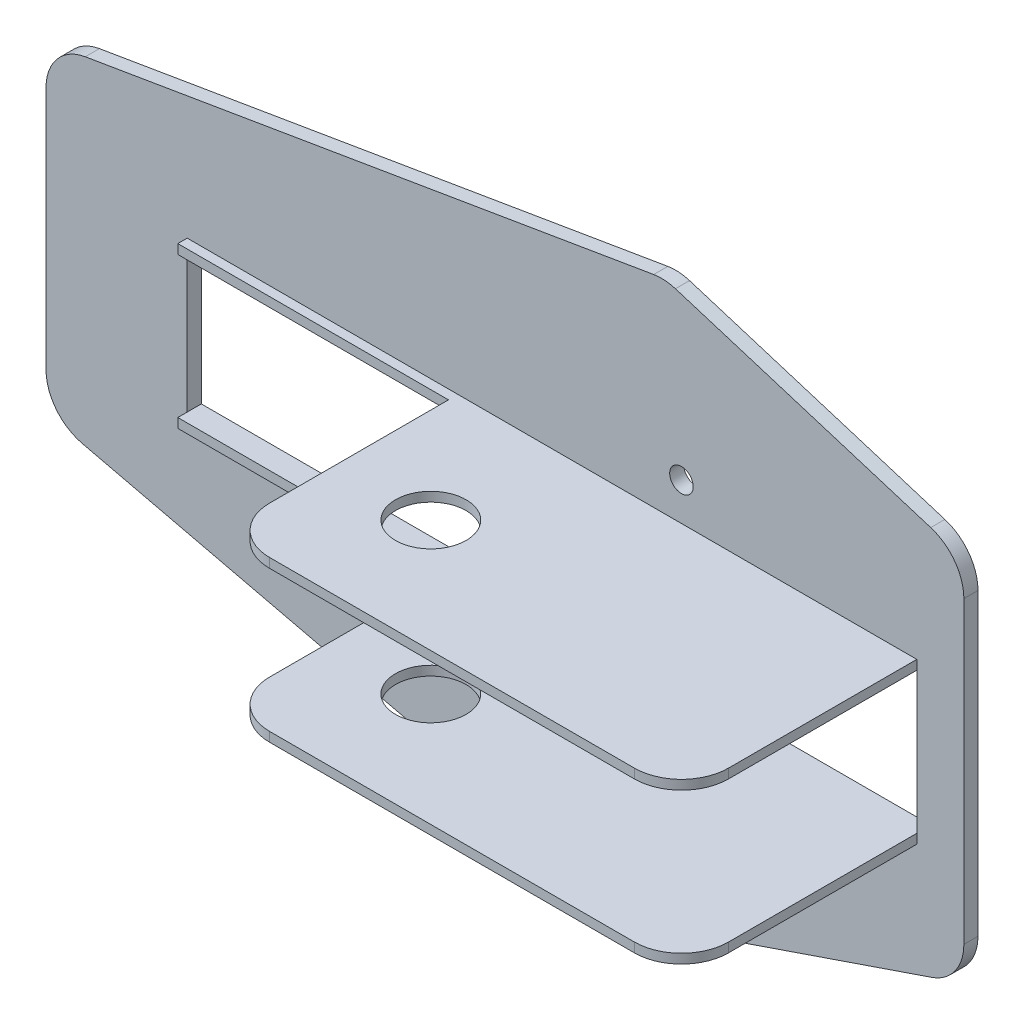
SolidWorks part; units mm, degrees
ref_plane "Płaszczyzna przednia" through (0, 0, 0) normal (0, 0, 1) x (1, 0, 0)
ref_plane "Płaszczyzna górna" through (0, 0, 0) normal (0, 1, 0) x (1, 0, 0)
ref_plane "Płaszczyzna prawa" through (0, 0, 0) normal (1, 0, 0) x (0, 0, -1)
sketch "Szkic1" plane through (0, 0, 0) normal (0, 0, 1) x (1, 0, 0)
  line L1 (-130, -75) -> (130, -75)
  line L2 (-130, -75) -> (-130, 75)
  line L3 (-130, 75) -> (130, 75)
  line L4 (130, -75) -> (130, 75)
  line L5 (-130, -75) -> (130, 75) construction
  line L6 (-130, 75) -> (130, -75) construction
  point P0 (0, 0)
  dimension "D1" = 150
  dimension "D2" = 260
extrude "Dodanie-wyciągnięcie1" add sketch "Szkic1" along normal blind 3
sketch "Szkic2" plane through (0, 0, 3) normal (0, 0, 1) x (1, 0, 0)
  line L0 (130, -75) -> (130, 75) construction
  line L2 (-35, -15) -> (120, -15)
  line L3 (-35, -15) -> (-35, 15)
  line L4 (-35, 15) -> (120, 15)
  line L5 (120, -15) -> (120, 15)
  line L6 (-35, -15) -> (120, 15) construction
  line L7 (-35, 15) -> (120, -15) construction
  circle A0 centre (70, 25) radius 2.5
  circle A1 centre (70, -25) radius 2.5
  point P7 (42.5, 0)
  dimension "D1" = 5
  dimension "D2" = 5
  dimension "D3" = 25
  dimension "D4" = 25
  dimension "D5" = 60
  dimension "D6" = 60
  dimension "D7" = 155
  dimension "D8" = 30
  dimension "D9" = 165
  dimension "D10" = 15
extrude "Wytnij-wyciągnięcie1" cut sketch "Szkic2" against normal blind 3
ref_plane "Płaszczyzna1" through (130, 75, 3) normal (0, 1, 0) x (1, 0, 0)
sketch "Szkic4" plane through (0, 0, 0) normal (0, 0, -1) x (-1, 0, 0)
  line L0 (-130, -30.4364) -> (-130, 33.1787)
  line L1 (-130, -75) -> (-130, 75) construction
  line L2 (-122.9621, 42.73) -> (-68.7231, 59.5512)
  line L3 (-64.1018, 59.8614) -> (56.6591, 39.5438)
  line L4 (65, 29.6824) -> (65, -22.1974)
  line L5 (57.2986, -31.9296) -> (-60.4177, -59.7322)
  line L6 (-65.9482, -59.4633) -> (-123.2319, -39.8997)
  line L7 (35, 15) -> (35, -15) construction
  line L8 (-120, 15) -> (35, 15) construction
  line L9 (35, -15) -> (-120, -15) construction
  line L10 (-130, 33.1787) -> (-130, 75)
  line L11 (-130, 75) -> (130, 75)
  line L12 (130, 75) -> (130, -75)
  line L13 (130, -75) -> (-130, -75)
  line L14 (-130, -75) -> (-130, -30.4364)
  arc A0 (-130, -30.4364) -> (-123.2319, -39.8997) centre (-120, -30.4364) ccw
  arc A1 (-122.9621, 42.73) -> (-130, 33.1787) centre (-120, 33.1787) ccw
  arc A2 (-60.4177, -59.7322) -> (-65.9482, -59.4633) centre (-62.7162, -50) cw
  arc A3 (-64.1018, 59.8614) -> (-68.7231, 59.5512) centre (-65.761, 50) ccw
  arc A4 (65, -22.1974) -> (57.2986, -31.9296) centre (55, -22.1974) cw
  arc A5 (56.6591, 39.5438) -> (65, 29.6824) centre (55, 29.6824) cw
  point P10 (-130, -37.5883)
  point P13 (-130, 40.5473)
  line M19 (-130, 75) -> (-130, -75)
  line M20 (-130, -75) -> (130, -75)
  line M21 (130, -75) -> (130, 75)
  line M22 (130, 75) -> (-130, 75)
  dimension "D1" = 10
  dimension "D2" = 10
  dimension "D3" = 10
  dimension "D5" = 35
  dimension "D4" = 30
  dimension "D6" = 35
extrude "Wytnij-wyciągnięcie3" cut sketch "Szkic4" against normal blind 3 contours L3 A5 L4 A4 L5 A2 L6 A0 A1 L2 A3 M19 M20 M21 M22
ref_plane "Płaszczyzna2" through (120, 15, 0) normal (0, 1, 0) x (1, 0, 0)
sketch "Szkic6" plane through (0, 0, 0) normal (0, 0, -1) x (-1, 0, 0)
  line L0 (-120, 15) -> (35, 15)
  line L1 (-111.75, 15) -> (-128.25, 15) construction
  line L2 (-120, -15) -> (-120, 15) construction
  line L3 (35, 15) -> (35, 17)
  line L4 (35, 17) -> (-120, 17)
  line L5 (-120, 15) -> (-120, 17)
  line L6 (1.65, 0) -> (-1.65, 0) construction
  line L7 (35, -15) -> (35, -17)
  line L8 (-120, -15) -> (-120, -17)
  line L9 (-120, -15) -> (35, -15)
  line L10 (35, -17) -> (-120, -17)
  dimension "D1" = 2
extrude "Dodanie-wyciągnięcie2" add sketch "Szkic6" against normal blind 5
sketch "Szkic7" plane through (0, 0, 5) normal (0, 0, 1) x (1, 0, 0)
  line L0 (42.5, 15) -> (42.5, 17)
  line L1 (120, 15) -> (-35, 15) construction
  line L2 (-35, 17) -> (120, 17) construction
  line L3 (42.5, 17) -> (120, 17)
  line L4 (120, 17) -> (120, 15)
  line L5 (128.25, 15) -> (111.75, 15) construction
  line L6 (120, 17) -> (120, 15) construction
  line L7 (120, 15) -> (42.5, 15)
extrude "Dodanie-wyciągnięcie3" add sketch "Szkic7" along normal blind 48
mirror "Lustro2" about plane through (0, 0, 0) normal (0, 1, 0) of "Dodanie-wyciągnięcie3"
sketch "Szkic10" plane through (0, -17, 0) normal (0, -1, 0) x (1, 0, 0)
  line L0 (42.5, 53) -> (22.5, 53)
  line L1 (22.5, 53) -> (22.5, 5)
  line L2 (42.5, 5) -> (-35, 5) construction
  line L3 (22.5, 5) -> (42.5, 5)
  line L4 (42.5, 5) -> (42.5, 53)
  dimension "D1" = 20
extrude "Dodanie-wyciągnięcie5" add sketch "Szkic10" against normal blind 2
mirror "Lustro3" about plane through (0, 0, 0) normal (0, 1, 0) of "Dodanie-wyciągnięcie5"
sketch "Szkic12" plane through (0, -17, 0) normal (0, -1, 0) x (-1, 0, 0)
  line L0 (-120, -53) -> (-120, -3) construction
  line L1 (-120, -53) -> (-22.5, -53) construction
  circle A0 centre (-42.75, -29) radius 7.5
  dimension "D3" = 15
  dimension "D1" = 77.25
  dimension "D2" = 24
extrude "Wytnij-wyciągnięcie4" cut sketch "Szkic12" against normal blind 40
fillet "Zaokrąglenie1" radius 10 4 edges at (22.5, -16, 53) (120, -16, 53) (120, 16, 53) (22.5, 16, 53)
